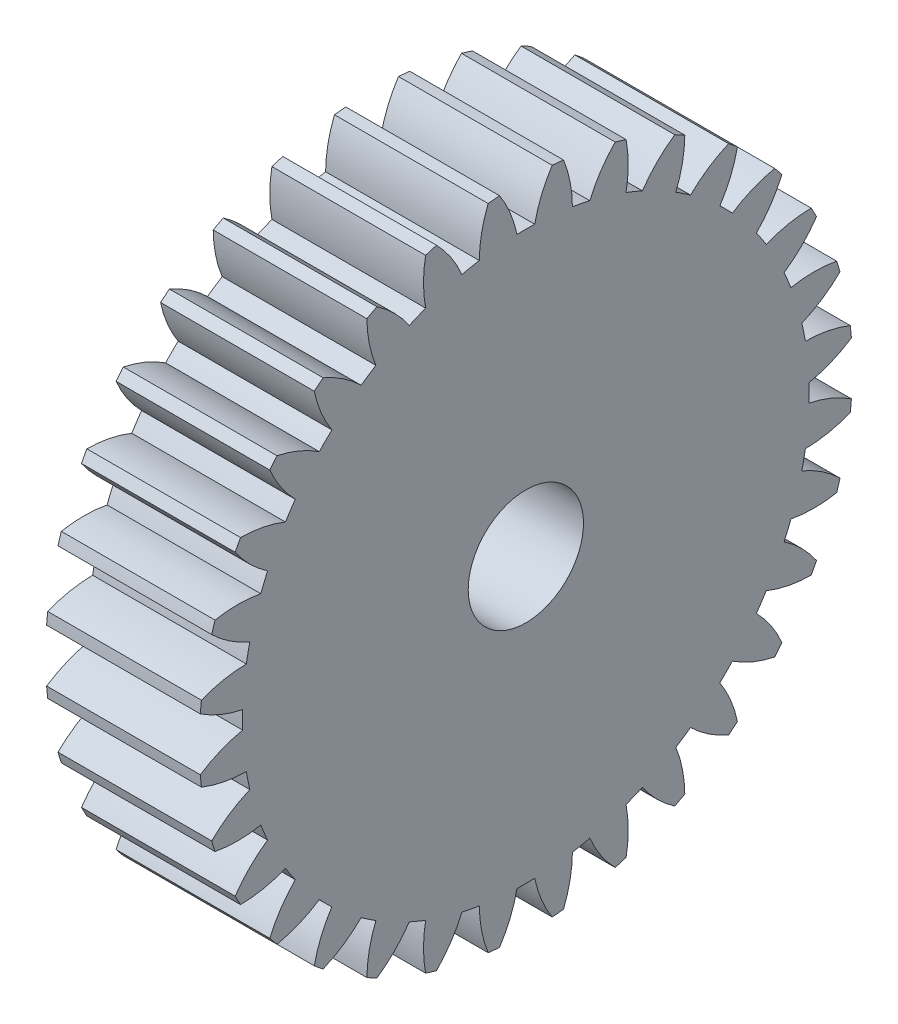
SolidWorks part; units mm, degrees
ref_plane "Plane1" through (0, 0, 0) normal (0, 0, 1) x (1, 0, 0)
ref_plane "Plane2" through (0, 0, 0) normal (0, 1, 0) x (1, 0, 0)
ref_plane "Plane3" through (0, 0, 0) normal (1, 0, 0) x (0, 0, -1)
sketch "HoldingSke" plane through (0, 0, 0) normal (0, 1, 0) x (1, 0, 0)
  line L0 (0, 0) -> (1.6961, -1.0598)
  line L1 (-15, 0) -> (100, 0) construction
  line L2 (0, 0) -> (-2.1039, 2.3779)
  line L3 (0, 0) -> (-11.863, 4.5341)
  line L4 (0, 0) -> (7.3237, 4.5764)
  line L5 (0, 0) -> (-46.8476, -17.4728)
  line L6 (0, 0) -> (-3.3159, -2.2372)
  line L7 (-2.1039, 2.3779) -> (8.6586, 51.2059)
  line L8 (-76.2, 54.61) -> (-75.7, 54.61)
  line L9 (-71.009, 38.7566) -> (-53.1078, 45.2721)
  line L10 (-76.2, 71.12) -> (104.1128, 71.12)
  line L11 (0, 0) -> (-4, 0)
  line L12 (-76.2, 101.6) -> (-76.181, 101.6)
  line L13 (24.9733, 27.94) -> (52.9518, 28.4284)
  line L14 (24.9733, 27.94) -> (24.9743, 27.94)
  line L15 (24.9733, 27.94) -> (100.4006, 29.5858)
  line L16 (-63.627, -0.5) -> (-12.827, -0.5)
  circle A0 centre (0, 0) radius 1.5
  circle A1 centre (0, 0) radius 7.374
  circle A2 centre (0, 0) radius 37.5
  circle A3 centre (0, 0) radius 1.5
  dimension "MHD" = 14.748
  dimension "Hub_dia" = 75
  dimension "Bore" = 3
  dimension "MBD" = 3
  dimension "Num_teeth" = 32
  dimension "Pitch" = 2
  dimension "Overall_len" = 50
  dimension "Show_teeth" = 32
  dimension "Thickness" = 4
  dimension "OAL" = 50.0001
  dimension "T_dim" = 0.5
  dimension "Ap" = 20
  dimension "H" = 19.05
  dimension "Pitch_radius" = 180.3128
  dimension "Width" = 4
  dimension "Backlash" = 0.019
  dimension "Addendum_fac" = 1
  dimension "Dedendum_fac" = 1.25
  dimension "Clearance_fac" = 0.25
  dimension "Dedendum_add" = 0.001
  dimension "Module" = 0.5
sketch "BasProSke" plane through (0, 0, 0) normal (0, 1, 0) x (1, 0, 0)
  line L0 (-10, 0) -> (60, 0) construction
  line L1 (0, 0) -> (0, 8.5)
  line L2 (0, 0) -> (4, 0)
  line L3 (4, 0) -> (4, 8.5)
  line L4 (4, 8.5) -> (0, 8.5)
  dimension "Thickness" = 4
  dimension "Diameter" = 17
revolve "Base-Revolve" add sketch "BasProSke" angle 360 about L0
sketch "TooCutSke" plane through (0, 0, 0) normal (1, 0, 0) x (0, 0, -1)
  line L1 (0, 0) -> (0, 107) construction
  line L2 (0, 0) -> (-0.4258, 7.9887) construction
  line L3 (0, 0) -> (-1.5667, 15.9069) construction
  line L4 (-0.4258, 7.9887) -> (-0.7833, 7.9534) construction
  arc A0 (0.2309, 7.3704) -> (-0.2309, 7.3704) centre (0, 0) ccw
  arc A1 (0.7014, 8.4965) -> (-0.7014, 8.4965) centre (0, 0) ccw
  circle A2 centre (0, 0) radius 8 construction
  circle A3 centre (0, 0) radius 7.5175 construction
  arc A4 (-0.2309, 7.3704) -> (-0.7014, 8.4965) centre (-3.3647, 6.7225) ccw
  arc A5 (0.7014, 8.4965) -> (0.2309, 7.3704) centre (3.3647, 6.7225) ccw
  dimension "Root_dia" = 14.748
  dimension "Overcut_dia" = 17.0508
  dimension "Pitch_dia" = 16
  dimension "Base_dia" = 15.0351
  dimension "Flank_rad" = 3.2
  dimension "Half_ang" = 5.625
  dimension "Half_CT" = 0.3593
extrude "ToothCut" cut sketch "TooCutSke" along normal through all
fillet "Breaks" [suppressed] radius 0.01
fillet "RootFillets" [suppressed] radius 0.126
pattern_circular "TeethCuts" count 32 every 11.25 about axis through (-10, 0, 0) along (1, 0, 0) of "ToothCut", "RootFillets", "Breaks"
sketch "HubNeaOneSke" plane through (0, 0, 0) normal (-1, 0, 0) x (0, 0, 1)
  circle A0 centre (0, 0) radius 7.374
  dimension "Diameter" = 14.748
extrude "HubNearOne" [suppressed] add sketch "HubNeaOneSke" along normal blind 46.0001
sketch "HubNeaBotSke" plane through (0, 0, 0) normal (-1, 0, 0) x (0, 0, 1)
  circle A0 centre (0, 0) radius 7.374
  dimension "Diameter" = 14.748
extrude "HubNearBoth" [suppressed] add sketch "HubNeaBotSke" along normal blind 23
ref_plane "FarPln" through (4, 0, 0) normal (1, 0, 0) x (0, 0, -1)
sketch "HubFarSke" plane through (4, 0, 0) normal (1, 0, 0) x (0, 0, -1)
  circle A0 centre (0, 0) radius 7.374
  dimension "Diameter" = 14.748
extrude "HubFar" [suppressed] add sketch "HubFarSke" along normal blind 23
sketch "BorSke" plane through (0, 0, 0) normal (1, 0, 0) x (0, 0, -1)
  circle A0 centre (0, 0) radius 1.5
  dimension "Diameter" = 3
extrude "Bore" cut sketch "BorSke" along normal mid plane 100.0001
sketch "KeySke" plane through (0, 0, 0) normal (1, 0, 0) x (0, 0, -1)
  line L0 (-0.6, 0) -> (-0.6, 2)
  line L1 (-0.6, 2) -> (0.6, 2)
  line L2 (0.6, 2) -> (0.6, 0)
  line L3 (0, 0) -> (0, 34) construction
  line L4 (-0.6, 0) -> (0.6, 0)
  dimension "Offset" = 2
  dimension "Width" = 1.2
extrude "Keyway" [suppressed] cut sketch "KeySke" along normal mid plane 100.0001
pattern_circular "Keyway2" [suppressed] count 2 every 90 about axis through (-10, 0, 0) along (1, 0, 0)
equation "' \"Module@HoldingSke\" = 6.35"
equation "' \"Num_teeth@HoldingSke\" = 12"
equation "' \"Ap@HoldingSke\" =  20"
equation "' \"Ap@HoldingSke\" = 20"
equation "' \"Width@HoldingSke\" = 0.5 * 25.4"
equation "' \"Hub_dia@HoldingSke\"= 1 * 25.4"
equation "' \"Hub_dia@HoldingSke\" = 1 * 25.4"
equation "' \"Overall_len@HoldingSke\" = 1.0 * 25.4"
equation "' \"Bore@HoldingSke\" = 0.75 * 25.4"
equation "' \"T_dim@HoldingSke\" = 0.1 * 25.4"
equation "' \"Width@KeySke\" = 0.25 * 25.4"
equation "' \"Show_teeth@HoldingSke\" = 13"
equation "' \"Backlash@HoldingSke\" = 0.009 * 25.4"
equation "' \"Addendum_fac@HoldingSke\" = 1.0"
equation "' \"Dedendum_fac@HoldingSke\" = 1.25"
equation "' \"Dedendum_add@HoldingSke\" = 0.00005 * 25.4"
equation "' \"Clearance_fac@HoldingSke\" = 0.25"
equation "\"Pitch@HoldingSke\" = 1 / \"Module@HoldingSke\""
equation "\"Overcut_dia@TooCutSke\" = (\"Num_teeth@HoldingSke\" + 2 * \"Addendum_fac@HoldingSke\") / \"Pitch@HoldingSke\" + 0.002 * 25.4"
equation "\"Pitch_dia@TooCutSke\" = \"Num_teeth@HoldingSke\" / \"Pitch@HoldingSke\""
equation "\"Base_dia@TooCutSke\" = \"Num_teeth@HoldingSke\" / \"Pitch@HoldingSke\" * cos((\"Ap@HoldingSke\"  * 3.14159265 / 180))"
equation "\"Root_dia@TooCutSke\" = (\"Num_teeth@HoldingSke\" + 2) / \"Pitch@HoldingSke\" - 2 * (\"Addendum_fac@HoldingSke\" + \"Dedendum_fac@HoldingSke\") / \"Pitch@HoldingSke\" - \"Dedendum_add@HoldingSke\" * 2"
equation "\"Half_ang@TooCutSke\" = 180 / \"Num_teeth@HoldingSke\""
equation "\"Half_CT@TooCutSke\" = \"Num_teeth@HoldingSke\" / \"Pitch@HoldingSke\" * sin((3.14159265 / 2 / \"Num_teeth@HoldingSke\")) / 2 - 7 * \"Backlash@HoldingSke\" / 4"
equation "\"Flank_rad@TooCutSke\" = \"Num_teeth@HoldingSke\" / \"Pitch@HoldingSke\" / 5"
equation "\"Radius@RootFillets\" = \"Clearance_fac@HoldingSke\" / \"Pitch@HoldingSke\" + \"Dedendum_add@HoldingSke\""
equation "\"Break_rad@Breaks\" = 0.02 / \"Pitch@HoldingSke\""
equation "\"Thickness@HoldingSke\" = \"Width@HoldingSke\""
equation "\"OAL@HoldingSke\" = \"Thickness@HoldingSke\""
equation "\"MHD@HoldingSke\" = (\"Num_teeth@HoldingSke\" + 2) / \"Pitch@HoldingSke\" - 2 * (\"Addendum_fac@HoldingSke\" + \"Dedendum_fac@HoldingSke\")  / \"Pitch@HoldingSke\" - \"Dedendum_add@HoldingSke\" * 2"
equation "\"MBD@HoldingSke\" = (\"Num_teeth@HoldingSke\" + 2) / \"Pitch@HoldingSke\" - 2 * (\"Addendum_fac@HoldingSke\" + \"Dedendum_fac@HoldingSke\")  / \"Pitch@HoldingSke\" - \"Dedendum_add@HoldingSke\" * 2 - 0.002 * 25.4"
equation "\"MHD@HoldingSke\" = ((sgn( \"MHD@HoldingSke\" - \"Hub_dia@HoldingSke\" )-1)*( \"MHD@HoldingSke\" - \"Hub_dia@HoldingSke\" ))/-2+ \"Hub_dia@HoldingSke\""
equation "\"MBD@HoldingSke\" = ((sgn( \"MBD@HoldingSke\" - \"Bore@HoldingSke\" )-1)*( \"MBD@HoldingSke\" - \"Bore@HoldingSke\" ))/-2+ \"Bore@HoldingSke\""
equation "\"OAL@HoldingSke\" = ((sgn( \"OAL@HoldingSke\" - \"Overall_len@HoldingSke\" )+1)*( \"OAL@HoldingSke\" - \"Overall_len@HoldingSke\" ))/2 + \"Overall_len@HoldingSke\" + 0.000002 * 25.4"
equation "\"Num_teeth@TeethCuts\" = int( \"Show_teeth@HoldingSke\" ) + 1"
equation "\"Num_teeth@TeethCuts\" = ((sgn( \"Num_teeth@TeethCuts\" - \"Num_teeth@HoldingSke\" )-1)*( \"Num_teeth@TeethCuts\" - \"Num_teeth@HoldingSke\" ))/-2+ \"Num_teeth@HoldingSke\""
equation "\"Num_teeth@TeethCuts\" = ((sgn( \"Num_teeth@TeethCuts\" - 2.0)+1)*( \"Num_teeth@TeethCuts\" - 2.0))/2 +2.0"
equation "\"Angle@TeethCuts\" = 360.0 / \"Num_teeth@HoldingSke\""
equation "\"Diameter@BasProSke\" = (\"Num_teeth@HoldingSke\" + 2 * \"Addendum_fac@HoldingSke\") / \"Pitch@HoldingSke\""
equation "\"Thickness@BasProSke\"  = \"Thickness@HoldingSke\""
equation "' \"Fillet_rad@BasProSke\" =  \"Thickness@HoldingSke\" * 0.05"
equation "' \"Fillet_rad@BasProSke\" = \"Thickness@HoldingSke\" * 0.05"
equation "\"MHD@HoldingSke\" = ((sgn( \"MHD@HoldingSke\" - \"Root_dia@TooCutSke\" )-1)*( \"MHD@HoldingSke\" - \"Root_dia@TooCutSke\" ))/-2+ \"Root_dia@TooCutSke\""
equation "\"Diameter@HubNeaOneSke\" = \"MHD@HoldingSke\""
equation "\"Length@HubNearOne\" = \"OAL@HoldingSke\" - \"Thickness@BasProSke\""
equation "\"Diameter@HubNeaBotSke\" = \"MHD@HoldingSke\""
equation "\"Length@HubNearBoth\" = ( \"OAL@HoldingSke\" - \"Thickness@BasProSke\" ) / 2.0"
equation "\"Thickness@FarPln\" = \"Thickness@BasProSke\""
equation "\"Diameter@HubFarSke\" = \"MHD@HoldingSke\""
equation "\"Length@HubFar\" = ( \"OAL@HoldingSke\" - \"Thickness@BasProSke\" ) / 2.0"
equation "\"Diameter@BorSke\" = \"MBD@HoldingSke\""
equation "\"D1@Bore\" = \"OAL@HoldingSke\" * 2.0"
equation "\"D1@Keyway\" = \"OAL@HoldingSke\" * 2.0"
equation "\"Offset@KeySke\" = \"T_dim@HoldingSke\" + \"MBD@HoldingSke\" / 2.0"
